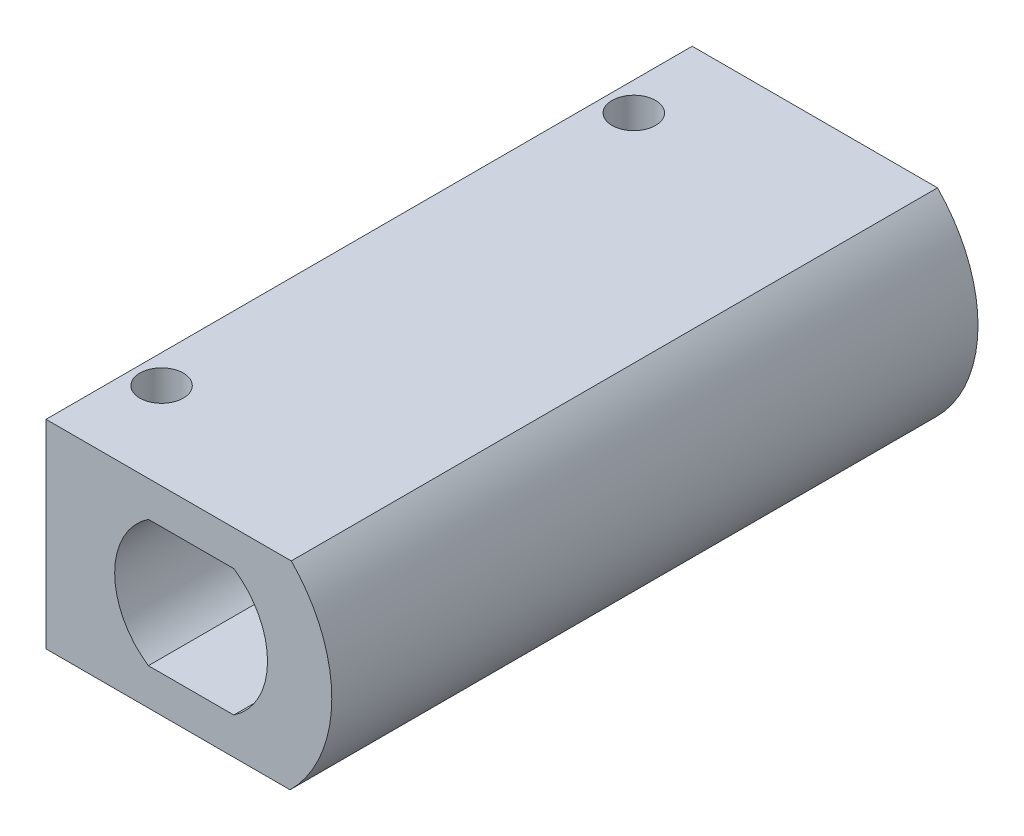
SolidWorks part; units mm, degrees
ref_plane "Alzado" through (0, 0, 0) normal (0, 0, 1) x (1, 0, 0)
ref_plane "Planta" through (0, 0, 0) normal (0, 1, 0) x (1, 0, 0)
ref_plane "Vista lateral" through (0, 0, 0) normal (1, 0, 0) x (0, 0, -1)
sketch "Croquis1" plane through (0, 0, 0) normal (0, 0, 1) x (1, 0, 0)
  line L1 (-22.1523, 15.7088) -> (-3.0323, 15.7088)
  line L2 (-22.1523, 15.7088) -> (-22.1523, -0.2912)
  line L3 (-22.1523, -0.2912) -> (-3.0323, -0.2912)
  line L4 (-3.0323, -0.1912) -> (-3.0323, -0.2912)
  line L5 (-6.5425, 13.9088) -> (-15.642, 13.9088)
  line L7 (-6.5425, 1.6088) -> (-15.642, 1.6088)
  arc A0 (-6.5425, 1.6088) -> (-6.5425, 13.9088) centre (-11.0923, 7.7588) ccw
  arc A1 (-15.642, 13.9088) -> (-15.642, 1.6088) centre (-11.0923, 7.7588) ccw
  arc A2 (-3.1321, -0.2912) -> (-3.0323, 15.7088) centre (-11.0923, 7.7588) ccw
  point P10 (-12.5923, -0.2912)
  dimension "D3" = 15.3
  dimension "D1" = 19.12
  dimension "D2" = 16
  dimension "D6" = 1.5
  dimension "D7" = 1.9
extrude "Saliente-Extruir1" add sketch "Croquis1" along normal blind 52 contours L3 A2 L1 L2 A1 L5 A0 L7
sketch "Croquis3" plane through (0, 0, 52) normal (0, 0, 1) x (1, 0, 0)
  line L1 (-22.1523, 15.7088) -> (-22.7679, 15.7088)
  line L2 (-22.1523, 15.7088) -> (-22.1523, -0.2912)
  line L3 (-22.1523, -0.2912) -> (-22.7679, -0.2912)
  line L4 (-22.7679, 15.7088) -> (-22.7679, -0.2912)
extrude "Saliente-Extruir2" add sketch "Croquis3" against normal blind 52
sketch "Croquis2" plane through (0, 15.7088, 0) normal (0, 1, 0) x (1, 0, 0)
  line L4 (-22.7679, -52) -> (-3.0323, -52) construction
  line L5 (-22.7679, 0) -> (-3.0323, 0) construction
  circle A0 centre (-20.4679, -7) radius 1.75
  circle A1 centre (-20.4679, -45) radius 1.75
  dimension "D1" = 3.5
  dimension "D2" = 3.5
  dimension "D3" = 2.3
  dimension "D4" = 2.3
  dimension "D5" = 7
  dimension "D6" = 7
  dimension "D7" = 38
extrude "Cortar-Extruir1" cut sketch "Croquis2" against normal blind 52
sketch "Croquis5" plane through (0, 0, 52) normal (0, 0, 1) x (1, 0, 0)
  line L1 (-4.9423, 12.8588) -> (-17.2423, 12.8588)
  line L2 (-4.9423, 12.8588) -> (-4.9423, 2.6588)
  line L3 (-4.9423, 2.6588) -> (-17.2423, 2.6588)
  line L4 (-17.2423, 12.8588) -> (-17.2423, 2.6588)
  line L5 (-4.9423, 12.8588) -> (-17.2423, 2.6588) construction
  line L6 (-4.9423, 2.6588) -> (-17.2423, 12.8588) construction
  circle A0 centre (-11.0923, 7.7588) radius 6.15
  circle A1 centre (-11.0923, 7.7588) radius 7.65
  arc M3 (-15.642, 1.6088) -> (-15.642, 13.9088) centre (-11.0923, 7.7588) cw
  line M4 (-15.642, 13.9088) -> (-6.5425, 13.9088)
  arc M5 (-6.5425, 13.9088) -> (-6.5425, 1.6088) centre (-11.0923, 7.7588) cw
  line M6 (-6.5425, 1.6088) -> (-15.642, 1.6088)
  dimension "D1" = 12.3
  dimension "D2" = 10.2
extrude "Saliente-Extruir3" add sketch "Croquis5" against normal blind 52 contours A0 L1 L4 M3 | L4 M3 | A0 L1 M4 M3 | A0 L1 M5 M4 | A0 L2 L1 M5 | L2 M5 | A0 L3 L2 M5 | A0 L3 M6 M5 | L3 A0 | A0 L3 M3 M6 | A0 L4 L3 M3 | A1 M6 | A1 M4 | L1 A0
sketch "Croquis4" plane through (-22.7679, 0, 0) normal (-1, 0, 0) x (0, 0, 1)
  line L1 (29.4455, 3.7558) -> (22.5545, 3.7558)
  line L2 (29.4455, 3.7558) -> (29.4455, 11.6618)
  line L3 (29.4455, 11.6618) -> (22.5545, 11.6618)
  line L4 (22.5545, 3.7558) -> (22.5545, 11.6618)
  line L5 (29.4455, 3.7558) -> (22.5545, 11.6618) construction
  line L6 (29.4455, 11.6618) -> (22.5545, 3.7558) construction
  point P0 (26, 7.7088)
extrude "Cortar-Extruir2" cut sketch "Croquis4" against normal blind 10
